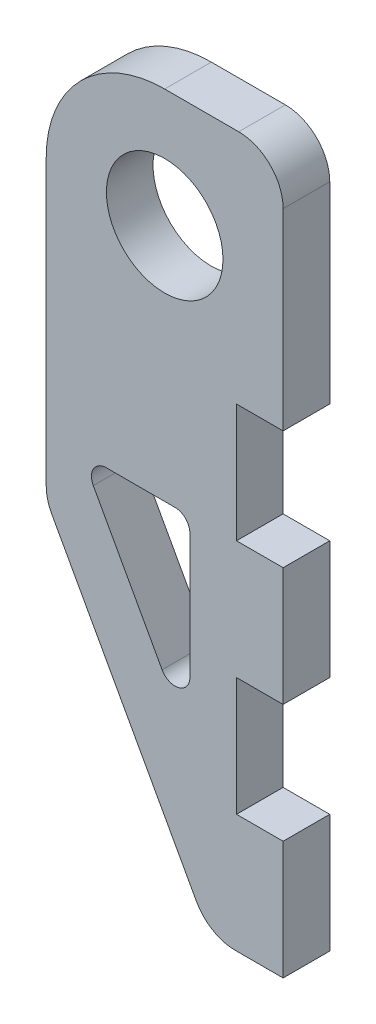
SolidWorks part; units mm, degrees
material "Hexcel AS4C (3000 Filaments)"
ref_plane "Front Plane" through (0, 0, 0) normal (0, 0, 1) x (1, 0, 0)
ref_plane "Top Plane" through (0, 0, 0) normal (0, 1, 0) x (1, 0, 0)
ref_plane "Right Plane" through (0, 0, 0) normal (1, 0, 0) x (0, 0, -1)
sketch "Sketch1" plane through (0, 0, 0) normal (0, 0, 1) x (1, 0, 0)
  line L1 (10.16, 6.35) -> (10.16, -10.16)
  line L2 (10.16, -10.16) -> (6.16, -10.16)
  line L3 (6.16, -10.16) -> (6.16, -20.32)
  line L4 (6.16, -20.32) -> (10.16, -20.32)
  line L5 (10.16, -20.32) -> (10.16, -30.48)
  line L6 (10.16, -30.48) -> (6.16, -30.48)
  line L7 (6.16, -30.48) -> (6.16, -40.64)
  line L8 (6.16, -40.64) -> (10.16, -40.64)
  line L9 (10.16, -40.64) -> (10.16, -50.8)
  line L10 (10.16, -50.8) -> (6.0627, -50.8)
  line L11 (2.7244, -48.8261) -> (-9.6884, -26.2575)
  line L14 (0, 10.16) -> (6.35, 10.16)
  line L15 (-10.16, 0) -> (-10.16, -24.4214)
  circle A0 centre (0, 0) radius 5
  arc A2 (-10.16, 0) -> (0, 10.16) centre (0, 0) cw
  arc A3 (6.0627, -50.8) -> (2.7244, -48.8261) centre (6.0627, -46.99) cw
  arc A4 (-9.6884, -26.2575) -> (-10.16, -24.4214) centre (-6.35, -24.4214) cw
  arc A5 (6.35, 10.16) -> (10.16, 6.35) centre (6.35, 6.35) cw
  point P5 (-10.16, -26.6641)
  point P16 (-10.16, -21.2443)
  point P20 (3.81, -50.8)
  point P23 (-10.16, -25.4)
  dimension "D1" = 10
  dimension "D2" = 10.16
  dimension "D9" = 3.81
  dimension "D3" = 25.4
  dimension "D4" = 4
  dimension "D5" = 50.8
  dimension "D6" = 10.16
  dimension "D7" = 6.35
  dimension "D8" = 10.16
extrude "Boss-Extrude2" add sketch "Sketch1" along normal blind 4
sketch "Sketch2" plane through (0, 0, 4) normal (0, 0, 1) x (1, 0, 0)
  line L0 (-6.1249, -22.3614) -> (-0.2228, -33.0925)
  line L5 (2.16, -32.4804) -> (2.16, -21.7494)
  line L6 (0.89, -20.4794) -> (-5.0121, -20.4794)
  line L7 (-9.6884, -26.2575) -> (2.7244, -48.8261) construction
  line L8 (6.16, -20.32) -> (6.16, -10.16) construction
  line L9 (-10.16, 0) -> (-10.16, -24.4214) construction
  arc A0 (-0.2228, -33.0925) -> (2.16, -32.4804) centre (0.89, -32.4804) ccw
  arc A1 (-6.1249, -22.3614) -> (-5.0121, -20.4794) centre (-5.0121, -21.7494) cw
  arc A2 (2.16, -21.7494) -> (0.89, -20.4794) centre (0.89, -21.7494) ccw
  point P1 (1.779, -35.4103)
  point P4 (-6.5341, -20.5201)
  point P15 (-7.16, -20.4794)
  dimension "D4" = 1.27
  dimension "D1" = 4
  dimension "D2" = 5
  dimension "D3" = 3
extrude "Cut-Extrude1" cut sketch "Sketch2" against normal up to next
